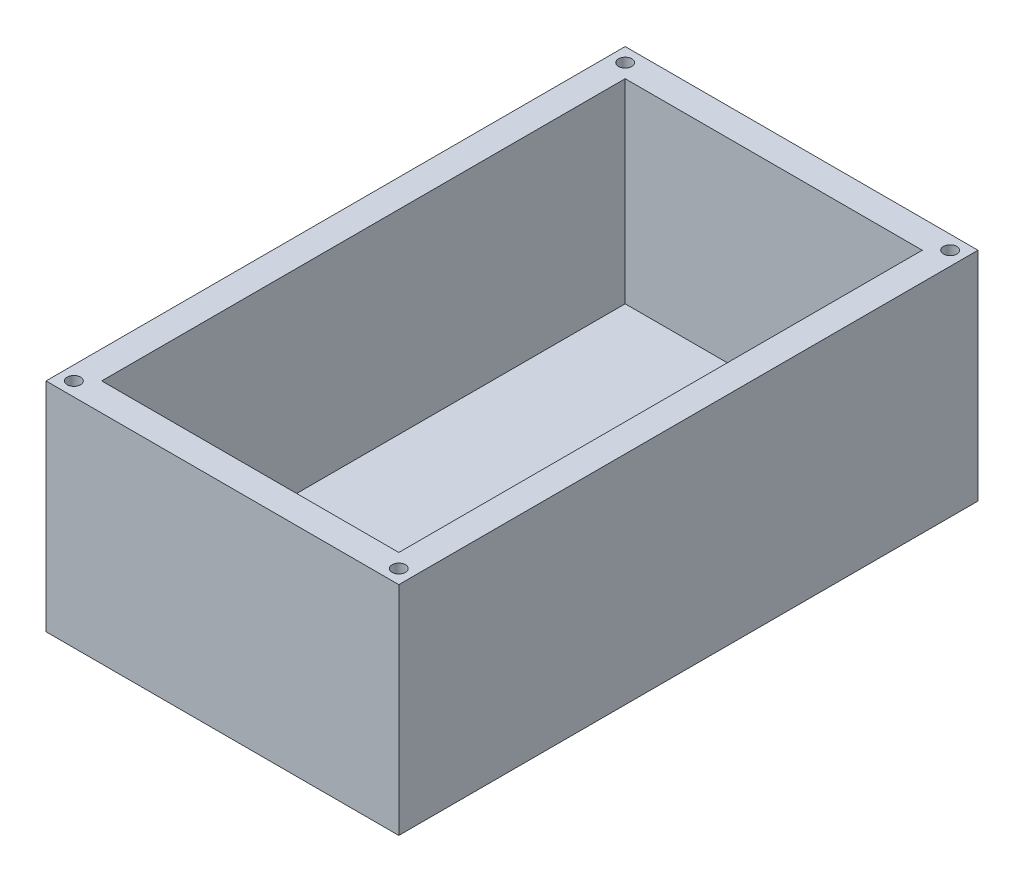
SolidWorks part; units mm, degrees
ref_plane "Piano frontale" through (0, 0, 0) normal (0, 0, 1) x (1, 0, 0)
ref_plane "Piano superiore" through (0, 0, 0) normal (0, 1, 0) x (1, 0, 0)
ref_plane "Piano destro" through (0, 0, 0) normal (1, 0, 0) x (0, 0, -1)
sketch "Schizzo1" plane through (0, 0, 0) normal (0, 1, 0) x (1, 0, 0)
  line L1 (2.4905, 3.4245) -> (65.8305, 3.4245)
  line L2 (2.4905, 3.4245) -> (2.4905, 107.4045)
  line L3 (2.4905, 107.4045) -> (65.8305, 107.4045)
  line L4 (65.8305, 3.4245) -> (65.8305, 107.4045)
  dimension "D1" = 103.98
  dimension "D2" = 63.34
extrude "Estrusione-Estrusione1" add sketch "Schizzo1" along normal blind 4
sketch "Schizzo2" plane through (0, 4, 0) normal (0, 1, 0) x (1, 0, 0)
  line L0 (2.4905, 107.4045) -> (2.4905, 3.4245) construction
  line L1 (2.4905, 107.4045) -> (65.8305, 107.4045)
  line L2 (2.4905, 107.4045) -> (2.4905, 3.4245)
  line L3 (2.4905, 3.4245) -> (65.8305, 3.4245)
  line L4 (65.8305, 107.4045) -> (65.8305, 3.4245)
  line L5 (7.4905, 102.4045) -> (7.4905, 8.4245)
  line L6 (7.4905, 8.4245) -> (60.8305, 8.4245)
  line L7 (60.8305, 102.4045) -> (60.8305, 8.4245)
  line L8 (7.4905, 102.4045) -> (60.8305, 102.4045)
  dimension "D1" = 5
extrude "Estrusione-Estrusione2" add sketch "Schizzo2" along normal blind 35
hole_wizard "Foro per Vite M2-1" positions "Schizzo3" profile "Schizzo4" hole size "M2" standard "Ansi Metric" end condition through all
sketch "Schizzo3" plane through (0, 39, 0) normal (0, 1, 0) x (1, 0, 0)
  line L0 (2.4905, 107.4045) -> (2.4905, 3.4245) construction
  line L1 (65.8305, 107.4045) -> (2.4905, 107.4045) construction
  line L2 (65.8305, 3.4245) -> (65.8305, 107.4045) construction
  line L3 (2.4905, 3.4245) -> (65.8305, 3.4245) construction
  point P0 (4.9905, 104.9045)
  point P2 (63.3305, 104.9045)
  point P4 (63.3305, 5.9245)
  point P6 (4.9905, 5.9245)
  dimension "D1" = 2.5
  dimension "D2" = 2.5
  dimension "D3" = 2.5
  dimension "D4" = 2.5
  dimension "D5" = 2.5
  dimension "D6" = 2.5
  dimension "D7" = 2.5
  dimension "D8" = 2.5
sketch "Schizzo4" plane through (4.9905, 39, -104.9045) normal (1, 0, 0) x (0, 0, 1)
  line L0 (0, 0) -> (0, 39)
  line L1 (0, 39) -> (1.2, 39)
  line L2 (1.2, 39) -> (1.2, 0)
  line L5 (1.2, 0) -> (0, 0)
  line L11 (0, -6.35) -> (0, 107.95) construction
  dimension "Thru Hole Dia." = 2.4
  dimension "Thru Hole Depth" = 39
sketch "Schizzo5" plane through (0, 0, -102.4045) normal (0, 0, 1) x (1, 0, 0)
  line L0 (2.4905, 0) -> (65.8305, 0) construction
  line L1 (17.4905, 4) -> (50.8305, 4)
  line L2 (17.4905, 4) -> (17.4905, 25.1523)
  line L3 (17.4905, 25.1523) -> (50.8305, 25.1523)
  line L4 (50.8305, 4) -> (50.8305, 25.1523)
  line L5 (2.4905, 39) -> (2.4905, 0) construction
  line L6 (65.8305, 39) -> (65.8305, 0) construction
  dimension "D1" = 4
  dimension "D2" = 15
  dimension "D3" = 15
